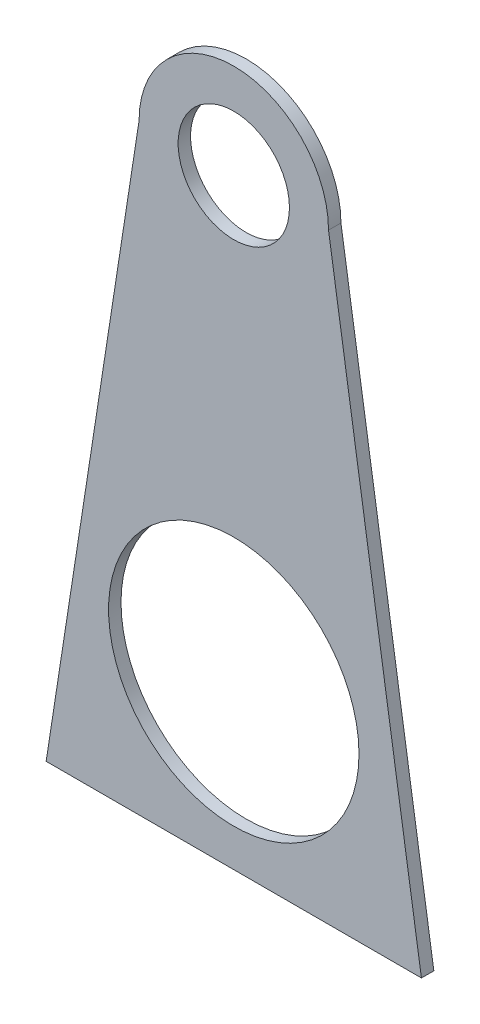
SolidWorks part; units mm, degrees
ref_plane "Front Plane" through (0, 0, 0) normal (0, 0, 1) x (1, 0, 0)
ref_plane "Top Plane" through (0, 0, 0) normal (0, 1, 0) x (1, 0, 0)
ref_plane "Right Plane" through (0, 0, 0) normal (1, 0, 0) x (0, 0, -1)
sketch "Sketch1" plane through (0, 0, 0) normal (0, 0, 1) x (1, 0, 0)
  line L0 (-24.2161, 0) -> (24.2161, 0) construction
  line L1 (0, 0) -> (0, -153.67) construction
  line L2 (47.961, -153.67) -> (-47.961, -153.67)
  line L3 (-47.961, -153.67) -> (-24.2161, 0)
  line L4 (24.2161, 0) -> (47.961, -153.67)
  arc A0 (-24.2161, 0) -> (24.2161, 0) centre (0, 0) cw
  circle A1 centre (0, 0) radius 14.224
  point P8 (0, -153.67)
  dimension "D1" = 28.448
  dimension "D2" = 153.67
extrude "Boss-Extrude1" add sketch "Sketch1" along normal blind 3.175
sketch "Sketch2" plane through (0, 0, 3.175) normal (0, 0, 1) x (1, 0, 0)
  line L0 (0, 0) -> (0, -153.67) construction
  line L1 (-47.961, -153.67) -> (47.961, -153.67) construction
  circle A0 centre (0, -112.0567) radius 32.004
  point P2 (0, 0)
  point P8 (0, -112.0567)
  dimension "D1" = 64.008
extrude "Cut-Extrude1" cut sketch "Sketch2" against normal up to surface (3.175 mm away) up to face at (0, -70.781, 0)
